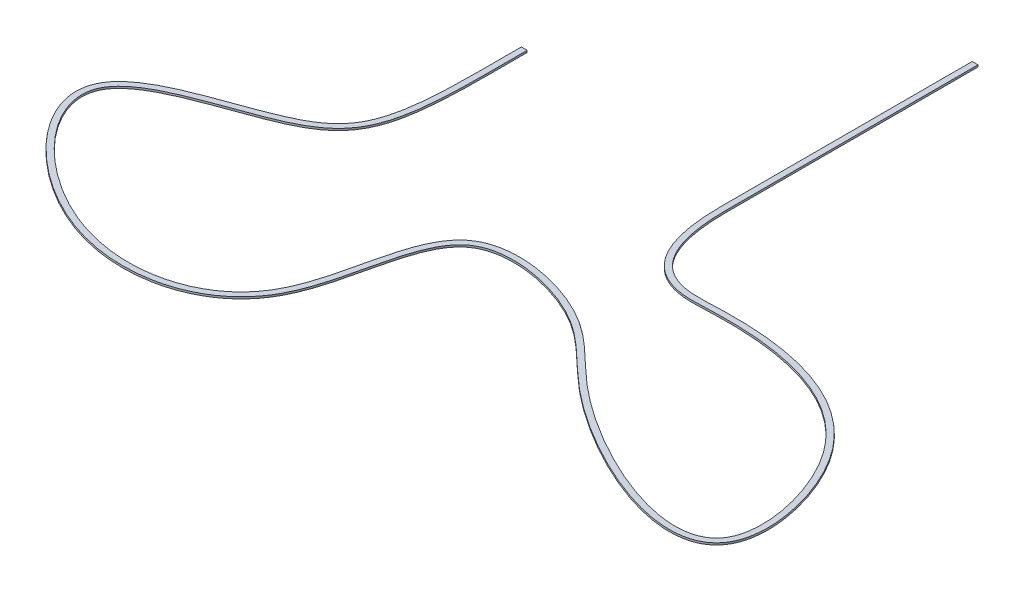
SolidWorks part; units mm, degrees
ref_plane "Front Plane" through (0, 0, 0) normal (0, 0, 1) x (1, 0, 0)
ref_plane "Top Plane" through (0, 0, 0) normal (0, 1, 0) x (1, 0, 0)
ref_plane "Right Plane" through (0, 0, 0) normal (1, 0, 0) x (0, 0, -1)
sketch "Sketch1" plane through (0, 0, 0) normal (0, 1, 0) x (1, 0, 0)
  line L0 (-1800, 0) -> (-1800, -200)
  line L1 (0, 0) -> (-3000, 0) construction
  line L2 (0, 0) -> (0, -2100) construction
  line L7 (0, -2100) -> (-3000, -2100) construction
  line L8 (-3000, 0) -> (-3000, -2100) construction
  line L9 (-3000, 0) -> (-3000, -200)
  line L10 (-1800, 0) -> (-1800, 1100)
  line L11 (-1770, 0) -> (-1770, 1100)
  line L12 (-1770, 0) -> (-1770, -200)
  line L13 (-3030, 0) -> (-3030, -200)
  line L14 (-3030, 0) -> (-3000, 0)
  line L15 (-1800, 1100) -> (-1770, 1100)
  spline S0 degree 3 poles (-1800, -200) (-1800, -543.776) (-1644.8578, -709.7008) (-1056.4658, -667.7604) (-390.715, -787.8273) (-115.8527, -2042.6037) (-1266.9515, -1497.6265) (-1650.9726, -1003.6724) (-2504.9874, -816.7564) (-2411.2342, -1892.3629) (-3401.5494, -2117.2993) (-4308.0653, -1186.3769) (-3088.7852, -965.5273) (-3000, -658.3861) (-3000, -200) knots 0 0 0 0 0.06809 0.085928 0.20346 0.276472 0.401964 0.455969 0.527915 0.623417 0.716394 0.819189 0.909166 1 1 1 1
  spline S1 degree 1 poles (-1770, -200) (-3030, -200) knots 0 0 1 1 construction
  spline S2 degree 3 poles (-1770, -200) (-1770, -202.4027) (-1769.9876, -207.2245) (-1769.9136, -216.7373) (-1769.729, -228.4741) (-1769.3619, -242.2847) (-1768.6799, -260.3458) (-1767.4705, -282.2596) (-1765.46, -307.5091) (-1762.9029, -331.723) (-1758.7819, -362.6435) (-1752.3298, -398.7657) (-1742.619, -438.1692) (-1731.0606, -473.7427) (-1717.7804, -505.6157) (-1697.9404, -543.3843) (-1669.4392, -582.1651) (-1629.8721, -616.9306) (-1592.3142, -637.4749) (-1559.3346, -649.3559) (-1533.1224, -656.05) (-1505.4464, -660.5967) (-1476.357, -663.0003) (-1445.4598, -663.5989) (-1413.1326, -662.9337) (-1385.1972, -661.7891) (-1362.3834, -660.8199) (-1345.0476, -660.1433) (-1327.5931, -659.5985) (-1304.2721, -659.0576) (-1274.9962, -658.7396) (-1239.7232, -658.9696) (-1192.555, -660.1423) (-1133.446, -663.3279) (-1062.6178, -670.2116) (-992.2347, -680.4699) (-922.6414, -694.4208) (-831.3705, -718.3757) (-721.0171, -759.1748) (-597.5576, -828.1332) (-504.8479, -904.3775) (-438.5005, -977.719) (-393.0395, -1039.1614) (-352.3903, -1107.1287) (-317.1273, -1179.6252) (-287.7001, -1254.9034) (-264.6575, -1331.166) (-248.5759, -1406.6615) (-240.0889, -1479.6876) (-239.9306, -1548.629) (-247.5256, -1601.4359) (-258.9608, -1640.1414) (-268.5575, -1662.6617) (-277.8384, -1679.5092) (-288.2508, -1695.5155) (-303.2276, -1713.5719) (-324.0141, -1731.9742) (-354.9521, -1752.0882) (-398.6435, -1769.1547) (-457.0111, -1778.4148) (-520.373, -1778.1485) (-588.0606, -1769.5794) (-683.1438, -1748.3581) (-809.1306, -1705.5393) (-964.7115, -1634.0942) (-1091.7202, -1562.636) (-1187.8731, -1501.164) (-1256.2926, -1453.6033) (-1309.4117, -1413.3434) (-1349.116, -1381.0643) (-1377.3086, -1356.9764) (-1404.1017, -1333.1266) (-1438.2738, -1301.7206) (-1478.6388, -1263.3788) (-1525.1382, -1219.3291) (-1571.5286, -1177.654) (-1611.6427, -1145.1627) (-1645.5682, -1120.6234) (-1672.1801, -1102.9651) (-1700.2115, -1086.0889) (-1729.9518, -1069.9586) (-1761.136, -1054.6981) (-1804.3393, -1035.6687) (-1860.8012, -1014.6408) (-1930.6236, -994.6988) (-2000.6349, -980.8791) (-2068.925, -973.9604) (-2133.5429, -974.6352) (-2182.6755, -981.9768) (-2218.209, -992.0556) (-2242.775, -1001.7244) (-2261.3723, -1011.5375) (-2275.0854, -1020.4626) (-2288.2041, -1030.198) (-2303.5287, -1043.8483) (-2326.0512, -1068.8421) (-2350.8065, -1105.906) (-2375.8436, -1158.8045) (-2397.0166, -1218.7089) (-2415.3534, -1284.065) (-2437.601, -1376.4116) (-2459.0767, -1473.5374) (-2485.2653, -1569.7259) (-2504.8281, -1628.319) (-2523.1683, -1673.5884) (-2538.4769, -1706.5619) (-2555.5335, -1738.3646) (-2574.6028, -1768.8221) (-2595.6098, -1797.5287) (-2626.035, -1833.469) (-2668.3669, -1873.9413) (-2725.245, -1915.2542) (-2808.1574, -1960.5623) (-2923.1876, -1998.7613) (-3048.7696, -2012.2037) (-3152.9527, -2007.9453) (-3232.3048, -1997.1877) (-3298.9076, -1981.864) (-3352.1509, -1965.7591) (-3405.2652, -1947.0588) (-3470.958, -1919.0769) (-3547.7499, -1879.1012) (-3621.5308, -1833.651) (-3714.5892, -1766.9588) (-3797.7019, -1692.9182) (-3866.8766, -1614.8986) (-3910.7691, -1555.1532) (-3945.6155, -1494.8605) (-3970.2492, -1434.5877) (-3981.0809, -1384.7567) (-3982.9667, -1345.4736) (-3980.704, -1316.476) (-3975.5271, -1292.9105) (-3969.3124, -1274.5939) (-3961.6852, -1256.701) (-3949.7322, -1235.525) (-3926.1185, -1204.0739) (-3889.3168, -1168.9757) (-3836.007, -1132.0015) (-3775.3718, -1098.8563) (-3709.1418, -1068.5715) (-3639.0725, -1040.3688) (-3566.9739, -1013.5743) (-3494.705, -987.5731) (-3424.1728, -961.7923) (-3368.4707, -940.048) (-3326.7672, -922.2662) (-3297.1703, -908.6868) (-3269.5541, -894.8404) (-3235.528, -875.9162) (-3197.9613, -851.1163) (-3160.1259, -818.7012) (-3128.5745, -782.579) (-3102.35, -741.3684) (-3080.7649, -693.5269) (-3063.4336, -637.6601) (-3052.3115, -583.4677) (-3045.2568, -535.05) (-3040.8429, -496.0925) (-3037.259, -454.3792) (-3034.4539, -409.7992) (-3032.7207, -370.1677) (-3031.6687, -336.9174) (-3031.0398, -311.193) (-3030.5638, -284.6676) (-3030.2885, -261.8841) (-3030.1372, -243.242) (-3030.0574, -229.0524) (-3030.0181, -217.048) (-3030.0026, -207.347) (-3030, -202.4447) (-3030, -200) knots 0 0 0 0 0.000488 0.000977 0.001953 0.00293 0.003906 0.005859 0.007812 0.009766 0.011719 0.015625 0.019531 0.023438 0.027344 0.03125 0.039062 0.046875 0.054688 0.058594 0.0625 0.066406 0.070312 0.074219 0.078125 0.082031 0.083984 0.085938 0.087891 0.089844 0.09375 0.097656 0.101562 0.109375 0.117188 0.125 0.132812 0.140625 0.15625 0.171875 0.1875 0.195312 0.203125 0.210938 0.21875 0.226562 0.234375 0.242188 0.25 0.257812 0.265625 0.269531 0.273438 0.275391 0.277344 0.28125 0.285156 0.289062 0.296875 0.304688 0.3125 0.320312 0.328125 0.34375 0.359375 0.375 0.382812 0.390625 0.398438 0.402344 0.40625 0.410156 0.414062 0.421875 0.429688 0.4375 0.445312 0.449219 0.453125 0.457031 0.460938 0.464844 0.46875 0.476562 0.484375 0.492188 0.5 0.507812 0.515625 0.519531 0.523438 0.527344 0.529297 0.53125 0.535156 0.539062 0.546875 0.554688 0.5625 0.570312 0.578125 0.59375 0.601562 0.609375 0.613281 0.617188 0.621094 0.625 0.628906 0.632812 0.640625 0.648438 0.65625 0.671875 0.6875 0.695312 0.703125 0.710938 0.714844 0.71875 0.726562 0.734375 0.742188 0.75 0.765625 0.773438 0.78125 0.789062 0.796875 0.804688 0.808594 0.8125 0.816406 0.818359 0.820312 0.824219 0.828125 0.835938 0.84375 0.851562 0.859375 0.867188 0.875 0.882812 0.890625 0.898438 0.902344 0.90625 0.910156 0.914062 0.921875 0.929688 0.9375 0.945312 0.953125 0.960938 0.96875 0.972656 0.976562 0.980469 0.984375 0.988281 0.990234 0.992188 0.994141 0.996094 0.99707 0.998047 0.999023 0.999512 1 1 1 1
  dimension "D1" = 3000
  dimension "D2" = 2100
  dimension "D3" = 1200
  dimension "D4" = 200
  dimension "D5" = 1100
  dimension "D6" = 30
extrude "Boss-Extrude3" add sketch "Sketch1" along normal blind 10
